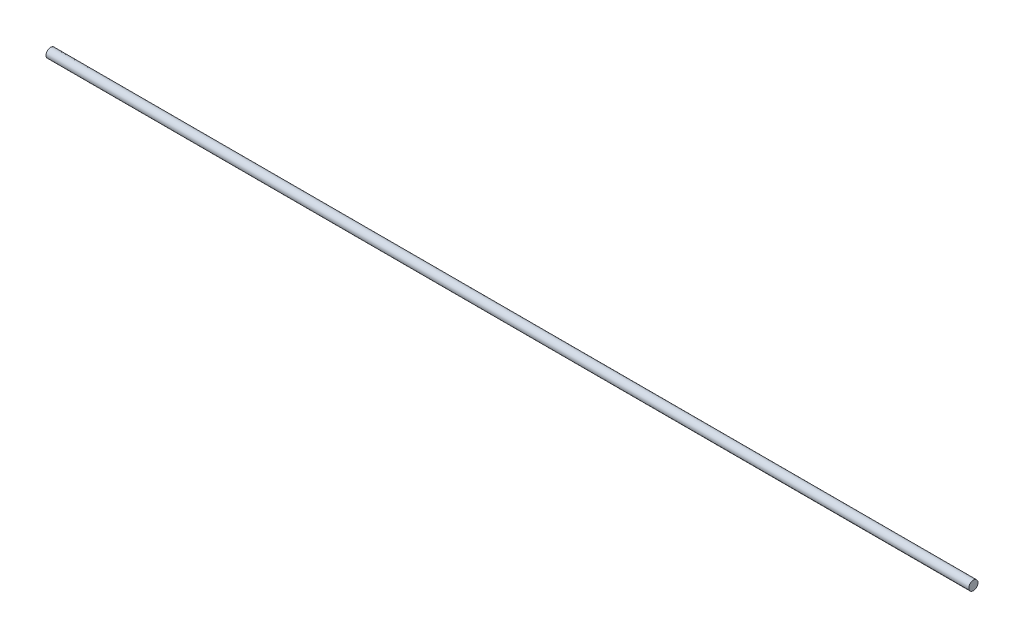
SolidWorks part; units mm, degrees
ref_plane "Front Plane" through (0, 0, 0) normal (0, 0, 1) x (1, 0, 0)
ref_plane "Top Plane" through (0, 0, 0) normal (0, 1, 0) x (1, 0, 0)
ref_plane "Right Plane" through (0, 0, 0) normal (1, 0, 0) x (0, 0, -1)
sketch "Sketch1" plane through (0, 0, 0) normal (1, 0, 0) x (0, 0, -1)
  circle A0 centre (0, 0) radius 0.5
  dimension "D1" = 1
extrude "Boss-Extrude1" add sketch "Sketch1" along normal blind 100 contours A0
sketch "Sketch2" plane through (100, 0, 0) normal (1, 0, 0) x (0, 0, -1)
  point P0 (0, 0)
sketch "Sketch3" plane through (0, 0, 0) normal (-1, 0, 0) x (0, 0, 1)
  point P0 (0, 0)
